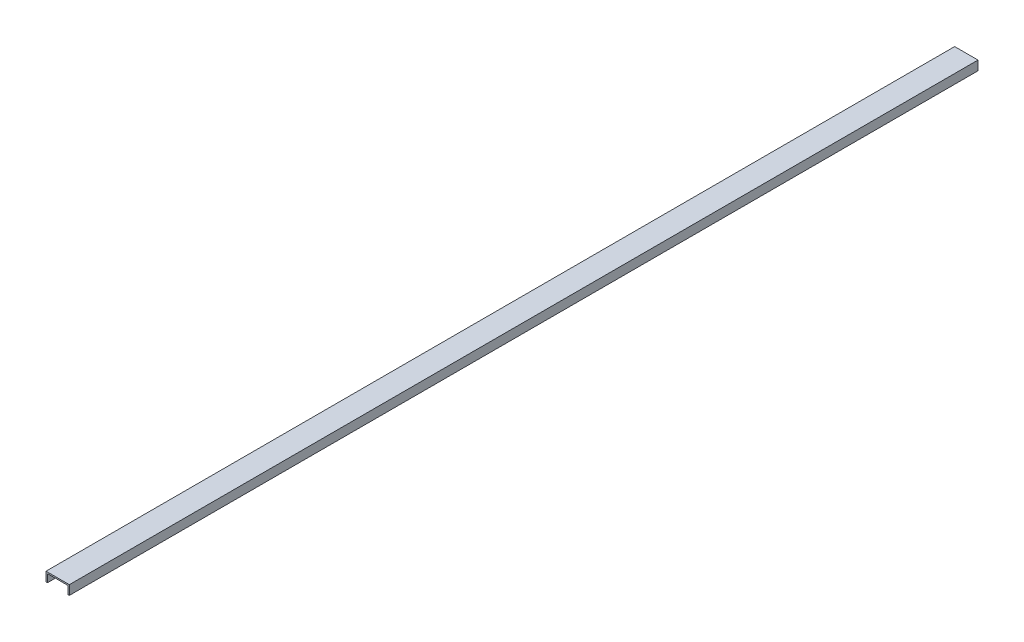
SolidWorks part; units mm, degrees
ref_plane "Front Plane" through (0, 0, 0) normal (0, 0, 1) x (1, 0, 0)
ref_plane "Top Plane" through (0, 0, 0) normal (0, 1, 0) x (1, 0, 0)
ref_plane "Right Plane" through (0, 0, 0) normal (1, 0, 0) x (0, 0, -1)
sketch "Sketch1" plane through (0, 0, 0) normal (0, 0, 1) x (1, 0, 0)
  line L0 (0, 0) -> (0, 20)
  line L1 (0, 20) -> (50, 20)
  line L2 (50, 20) -> (50, 0)
  line L3 (50, 0) -> (47, 0)
  line L4 (47, 0) -> (47, 17)
  line L5 (47, 17) -> (3, 17)
  line L6 (3, 17) -> (3, 0)
  line L7 (3, 0) -> (0, 0)
  dimension "D1" = 50
  dimension "D2" = 20
  dimension "D3" = 3
  dimension "D4" = 3
extrude "Boss-Extrude1" add sketch "Sketch1" along normal blind 1825
sketch "Sketch2" plane through (0, 0, 1825) normal (0, 0, 1) x (1, 0, 0)
  line L0 (0, 0) -> (0, 20)
  line L1 (0, 20) -> (50, 20)
  line L2 (50, 20) -> (50, 0)
  line L3 (50, 0) -> (47, 0)
  line L4 (47, 0) -> (47, 17)
  line L5 (47, 17) -> (3, 17)
  line L6 (3, 17) -> (3, 0)
  line L7 (3, 0) -> (0, 0)
extrude "Down" add sketch "Sketch2" along normal blind 47
sketch "Sketch3" plane through (0, 0, 0) normal (0, 0, -1) x (-1, 0, 0)
  line L0 (-50, 0) -> (-50, 20)
  line L1 (-50, 20) -> (0, 20)
  line L2 (0, 20) -> (0, 0)
  line L3 (0, 0) -> (-3, 0)
  line L4 (-3, 0) -> (-3, 17)
  line L5 (-3, 17) -> (-47, 17)
  line L6 (-47, 17) -> (-47, 0)
  line L7 (-47, 0) -> (-50, 0)
extrude "Up" add sketch "Sketch3" along normal blind 75
equation "\"boxWidth\"=1930.0"
equation "\"D1@Boss-Extrude1\"= \"indoorHeight\" + \"indoorHeight_para\" - 90 - 50"
equation "\"start\"=700.0"
equation "\"CarBeamWidth\"=700.0"
equation "\"WheelWidth\"=650.0"
equation "\"Wheel_FrontBoxDistance\"=1390.0"
equation "\"boxLength\"=5100.0"
equation "\"MetalSheet_3mm_length\"=5030.0"
equation "\"MetalSheet_3mm_width\"=1923.0"
equation "\"MetalSheet_3mm_FloorCut_L_length\"=1764.0"
equation "\"MetalSheet_3mm_FloorCut_L_disdance\"=1665.0"
equation "\"MetalSheet_3mm_FloorCut_R_length\"=1764.0"
equation "\"MetalSheet_3mm_FloorCut_R_disdance\"=1665.0"
equation "\"indoorHeight\"=1940.0"
equation "\"indoorHeight_para\"=25.0"
equation "\"rearLightHeight_para\"=265.0"
equation "\"doorColumnBar_A_FR_3mm_length_Cut\"=2310.0"
equation "\"A\"=0.0"
equation "\"haveDoor_R\"=1"
equation "\"side_door_bottom_R_3mm_length\"=1934.0"
equation "\"side_door_bottom_R_3mm_toFrontDistance\"=1583.0"
equation "\"1Bar_Side_RF_3mm_length\"=1493.0"
equation "\"1Bar_Side_RB_3mm_length\"=1493.0"
equation "\"DoorSeparator_RF_3mm_withHinge_toFrontDistance\"=1673.0"
equation "\"DoorSeparator_RF_3mm_withHinge_exist\"=1"
equation "\"DoorSeparator_RB_3mm_withHinge_toFrontDistance\"=3427.0"
equation "\"DoorSeparator_RB_3mm_withHinge_exist\"=1"
equation "\"Door_R1_L_open_Single_toFrontDistance\"=2547.5"
equation "\"Door_R1_L_open_Single_exist\"=1"
equation "\"door_base_long7_R1_L_open_Single_height\"=1890.0"
equation "\"door_base_short7_R1_L_open_Single_height\"=1890.0"
equation "\"door_base_short7_R1_L_open_Single_width\"=864"
equation "\"Door_R1_R_open_Single_toFrontDistance\"=3422.0"
equation "\"Door_R1_R_open_Single_exist\"=1"
equation "\"door_base_long7_R1_R_open_Single_height\"=1890.0"
equation "\"door_base_short7_R1_R_open_Single_height\"=1890.0"
equation "\"door_base_short7_R1_R_open_Single_width\"=864"
equation "\"x\"=66.0"
equation "\"door_base_double_BL_height\"=1890.0"
equation "\"door_base_short7_BL_Single_height\"=1890.0"
equation "\"door_base_short7_BL_Single_width\"=864"
equation "\"door_base_long7_BR_Single_height\"=1890.0"
equation "\"door_base_short7_BR_Single_height\"=1890.0"
equation "\"door_base_short7_BR_Single_width\"=864"
equation "\"da\"=62.0"
equation "\"SquareTube_length\"=1923.0"
equation "\"channelSteel_length\"=5030.0"
equation "\"SquareTube_inFront_AvgDistance\"=285.0"
equation "\"SquareTube_inFront_TotalCount\"=5"
equation "\"SquareTube_inFront1_cutDepth50_R\"=0.5"
equation "\"SquareTube_inFront1_cutDepth50_L\"=0.5"
equation "\"SquareTube_inFront2_cutDepth50_R\"=0.5"
equation "\"SquareTube_inFront2_cutDepth50_L\"=0.5"
equation "\"SquareTube_inFront3_cutDepth50_R\"=0.5"
equation "\"SquareTube_inFront3_cutDepth50_L\"=0.5"
equation "\"SquareTube_inFront4_cutDepth50_R\"=0.5"
equation "\"SquareTube_inFront4_cutDepth50_L\"=0.5"
equation "\"SquareTube_inFront5_cutDepth50_R\"=50"
equation "\"SquareTube_inFront5_cutDepth50_L\"=50"
equation "\"SquareTube_inFront6_cutDepth50_R\"=50"
equation "\"SquareTube_inFront6_cutDepth50_L\"=50"
equation "\"SquareTube_inFront7_cutDepth50_R\"=50"
equation "\"SquareTube_inFront7_cutDepth50_L\"=50"
equation "\"SquareTube_inFront8_cutDepth50_R\"=50"
equation "\"SquareTube_inFront8_cutDepth50_L\"=50"
equation "\"SquareTube_inFront9_cutDepth50_R\"=50"
equation "\"SquareTube_inFront9_cutDepth50_L\"=50"
equation "\"SquareTube_inFront10_cutDepth50_R\"=50"
equation "\"SquareTube_inFront10_cutDepth50_L\"=50"
equation "\"SquareTube_inFront11_cutDepth50_R\"=50"
equation "\"SquareTube_inFront11_cutDepth50_L\"=50"
equation "\"SquareTube_inFront12_cutDepth50_R\"=50"
equation "\"SquareTube_inFront12_cutDepth50_L\"=50"
equation "\"SquareTube_inFront13_cutDepth50_R\"=50"
equation "\"SquareTube_inFront13_cutDepth50_L\"=50"
equation "\"SquareTube_inFront14_cutDepth50_R\"=50"
equation "\"SquareTube_inFront14_cutDepth50_L\"=50"
equation "\"SquareTube_inBack_AvgDistance\"=333.125"
equation "\"SquareTube_inBack_TotalCount\"=9"
equation "\"SquareTube_inBack1_cutDepth50_R\"=50"
equation "\"SquareTube_inBack1_cutDepth50_L\"=50"
equation "\"SquareTube_inBack2_cutDepth50_R\"=50"
equation "\"SquareTube_inBack2_cutDepth50_L\"=50"
equation "\"SquareTube_inBack3_cutDepth50_R\"=50"
equation "\"SquareTube_inBack3_cutDepth50_L\"=50"
equation "\"SquareTube_inBack4_cutDepth50_R\"=50"
equation "\"SquareTube_inBack4_cutDepth50_L\"=50"
equation "\"SquareTube_inBack5_cutDepth50_R\"=50"
equation "\"SquareTube_inBack5_cutDepth50_L\"=50"
equation "\"SquareTube_inBack6_cutDepth50_R\"=0.5"
equation "\"SquareTube_inBack6_cutDepth50_L\"=0.5"
equation "\"SquareTube_inBack7_cutDepth50_R\"=0.5"
equation "\"SquareTube_inBack7_cutDepth50_L\"=0.5"
equation "\"SquareTube_inBack8_cutDepth50_R\"=0.5"
equation "\"SquareTube_inBack8_cutDepth50_L\"=0.5"
equation "\"doorColumnBar_A_FL_3mm_length_Cut\"=2310.0"
equation "\"B\"=0.0"
equation "\"haveDoor_L\"=1"
equation "\"side_door_bottom_L_3mm_length\"=1934.0"
equation "\"side_door_bottom_L_3mm_toFrontDistance\"=1583.0"
equation "\"1Bar_Side_LF_3mm_length\"=1493.0"
equation "\"1Bar_Side_LB_3mm_length\"=1493.0"
equation "\"DoorSeparator_LF_3mm_withHinge_toFrontDistance\"=1673.0"
equation "\"DoorSeparator_LF_3mm_withHinge_exist\"=1"
equation "\"DoorSeparator_LB_3mm_withHinge_toFrontDistance\"=3427.0"
equation "\"DoorSeparator_LB_3mm_withHinge_exist\"=1"
equation "\"Door_L1_L_open_Single_toFrontDistance\"=3422.0"
equation "\"Door_L1_L_open_Single_exist\"=1"
equation "\"door_base_long7_L1_L_open_Single_height\"=1890.0"
equation "\"door_base_short7_L1_L_open_Single_height\"=1890.0"
equation "\"door_base_short7_L1_L_open_Single_width\"=864"
equation "\"Door_L1_R_open_Single_toFrontDistance\"=2547.5"
equation "\"Door_L1_R_open_Single_exist\"=1"
equation "\"door_base_long7_L1_R_open_Single_height\"=1890.0"
equation "\"door_base_short7_L1_R_open_Single_height\"=1890.0"
equation "\"door_base_short7_L1_R_open_Single_width\"=864"
equation "\"D1@Down\" = IIF (  ( \"haveDoor_R\" )  = 1 , 60 , 70 ) "
equation "\"D1@Up\"= IIF ( ( \"haveDoor_R\" ) = 1 , 75 , 65 )"
